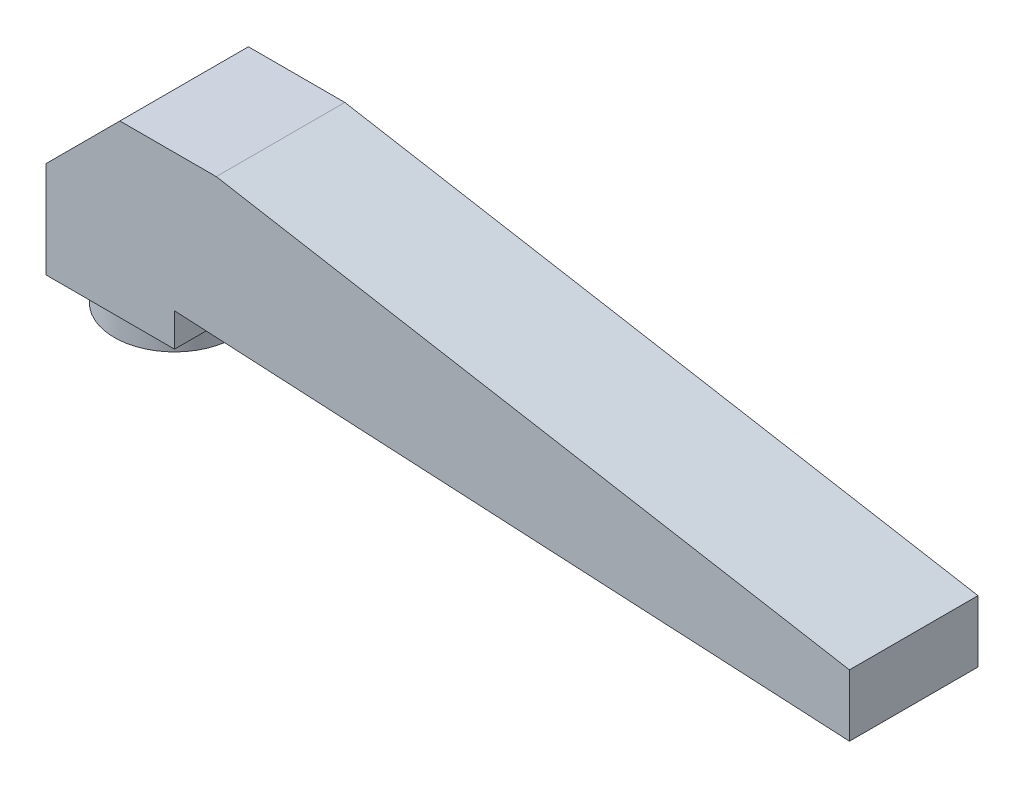
SolidWorks part; units mm, degrees
ref_plane "Front Plane" through (0, 0, 0) normal (0, 0, 1) x (1, 0, 0)
ref_plane "Top Plane" through (0, 0, 0) normal (0, 1, 0) x (1, 0, 0)
ref_plane "Right Plane" through (0, 0, 0) normal (1, 0, 0) x (0, 0, -1)
sketch "Sketch1" plane through (0, 0, 0) normal (0, 0, 1) x (1, 0, 0)
  line L0 (0, 296.5265) -> (0, 0) construction
  line L1 (0, 0) -> (660.9736, 0) construction
  line L2 (0, 0) -> (0, 60)
  line L3 (0, 60) -> (45.9619, 105.9619)
  line L4 (45.9619, 105.9619) -> (105.9619, 105.9619)
  line L5 (105.9619, 105.9619) -> (500, 37.1578)
  line L6 (500, 37.1578) -> (500, -1.3165)
  line L7 (0, 0) -> (80, 0)
  line L8 (80, 0) -> (80, 20.6948)
  line L9 (80, 20.6948) -> (500, -1.3165)
  dimension "D1" = 500
  dimension "D2" = 87
  dimension "D3" = 80
  dimension "D4" = 45
  dimension "D5" = 60
  dimension "D6" = 400
  dimension "D7" = 65
  dimension "D8" = 60
extrude "Boss-Extrude1" add sketch "Sketch1" along normal mid plane 80
sketch "Sketch2" plane through (0, 0, 0) normal (0, -1, 0) x (1, 0, 0)
  line L0 (0, 0) -> (80, 0) construction
  line L1 (80, 40) -> (80, -40) construction
  circle A0 centre (40, 0) radius 37.5
  dimension "D1" = 75
extrude "Boss-Extrude2" add sketch "Sketch2" along normal blind 15 separate body
